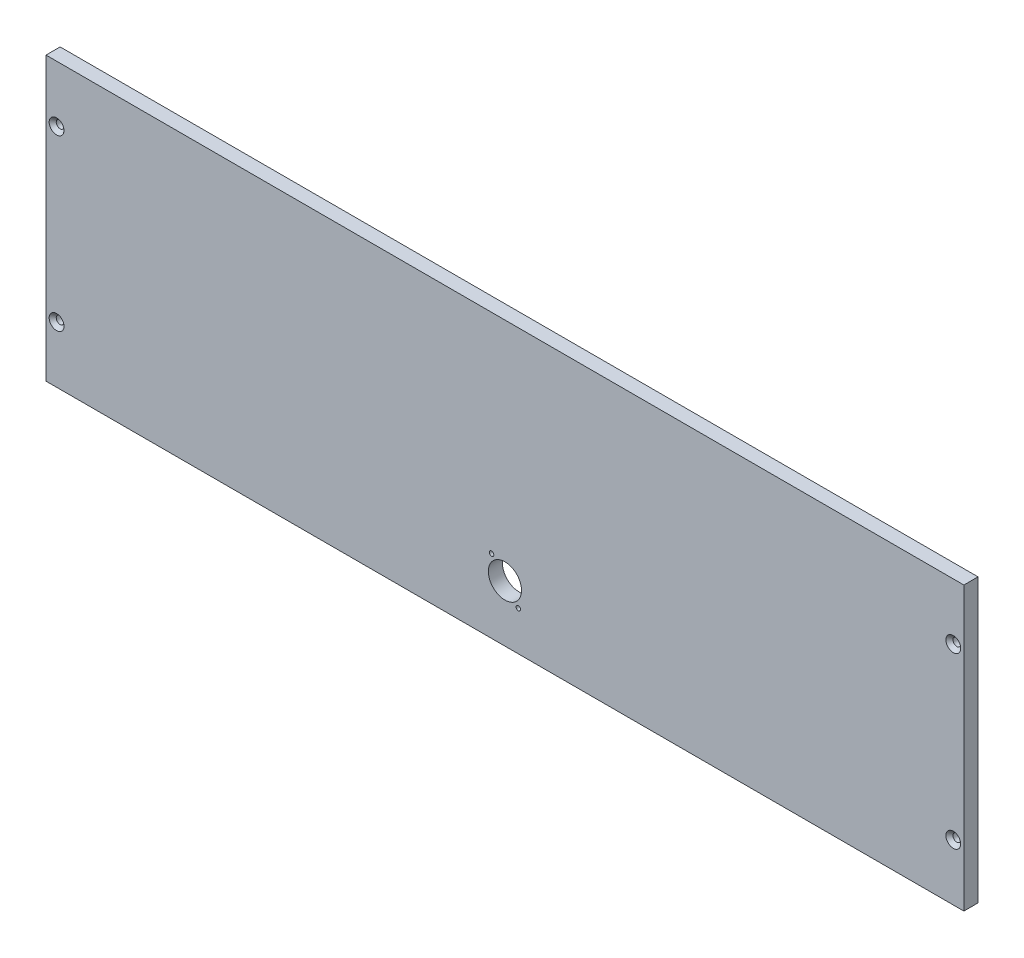
SolidWorks part; units mm, degrees
ref_plane "Plan de face" through (0, 0, 0) normal (0, 0, 1) x (1, 0, 0)
ref_plane "Plan de dessus" through (0, 0, 0) normal (0, 1, 0) x (1, 0, 0)
ref_plane "Plan de droite" through (0, 0, 0) normal (1, 0, 0) x (0, 0, -1)
sketch "Esquisse1" plane through (0, 0, 0) normal (0, 0, 1) x (1, 0, 0)
  line L1 (0, 0) -> (650, 0)
  line L2 (0, 0) -> (0, 200)
  line L3 (0, 200) -> (650, 200)
  line L4 (650, 0) -> (650, 200)
  dimension "D1" = 200
  dimension "D2" = 650
extrude "Boss.-Extru.1" add sketch "Esquisse1" along normal blind 10
sketch "Esquisse2" plane through (0, 0, 10) normal (0, 0, 1) x (1, 0, 0)
  line L0 (0, 200) -> (0, 0) construction
  line L1 (650, 200) -> (0, 200) construction
  line L2 (0, 0) -> (650, 0) construction
  line L3 (650, 0) -> (650, 200) construction
  circle A0 centre (7.5, 160) radius 2.75
  circle A1 centre (642.5, 160) radius 2.75
  circle A2 centre (7.5, 40) radius 2.75
  circle A3 centre (642.5, 40) radius 2.75
  dimension "D1" = 5.5
  dimension "D2" = 5.5
  dimension "D3" = 5.5
  dimension "D4" = 5.5
  dimension "D5" = 7.5
  dimension "D6" = 7.5
  dimension "D7" = 40
  dimension "D8" = 40
  dimension "D9" = 40
  dimension "D10" = 40
  dimension "D11" = 7.5
  dimension "D12" = 7.5
extrude "Enlèv. mat.-Extru.1" cut sketch "Esquisse2" against normal blind 10
chamfer "Chanfrein1" distance 2.5 angle 45 4 edges at (10.25, 160, 10) (10.25, 40, 10) (645.25, 40, 10) (645.25, 160, 10)
sketch "Esquisse3" plane through (0, 0, 10) normal (0, 0, 1) x (1, 0, 0)
  line L0 (0, 0) -> (650, 0) construction
  line L1 (334.5004, 28.0006) -> (325, 40)
  line L2 (325, 40) -> (315.4996, 51.9994)
  line L3 (325, 40) -> (265.8175, 40)
  line L4 (325, 40) -> (364.3682, 40)
  circle A0 centre (325, 40) radius 11.75
  circle A1 centre (315.4996, 51.9994) radius 1.6
  circle A2 centre (334.5004, 28.0006) radius 1.6
  point P4 (325, 0)
  dimension "D1" = 23.5
  dimension "D4" = 3.2
  dimension "D5" = 3.2
  dimension "D2" = 0
  dimension "D3" = 40
  dimension "D6" = 30.61
  dimension "D7" = 15.305
  dimension "D8" = 51.63
  dimension "D9" = 180
  dimension "D10" = 51.63
  dimension "D11" = 15.305
extrude "Enlèv. mat.-Extru.2" cut sketch "Esquisse3" against normal blind 10
